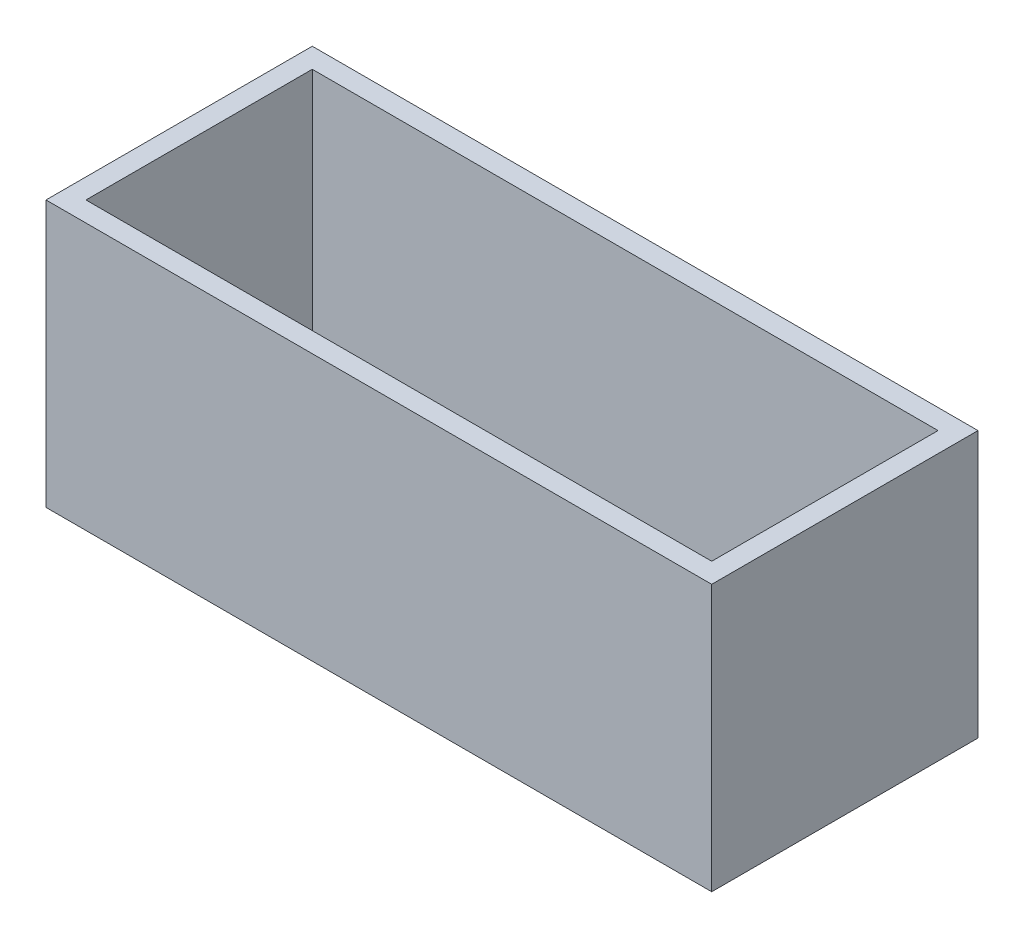
SolidWorks part; units mm, degrees
ref_plane "Front Plane" through (0, 0, 0) normal (0, 0, 1) x (1, 0, 0)
ref_plane "Top Plane" through (0, 0, 0) normal (0, 1, 0) x (1, 0, 0)
ref_plane "Right Plane" through (0, 0, 0) normal (1, 0, 0) x (0, 0, -1)
sketch "Sketch2" plane through (0, 0, 0) normal (0, 1, 0) x (1, 0, 0)
  line L1 (-50, -20) -> (50, -20)
  line L2 (-50, -20) -> (-50, 20)
  line L3 (-50, 20) -> (50, 20)
  line L4 (50, -20) -> (50, 20)
  line L5 (-50, -20) -> (50, 20) construction
  line L6 (-50, 20) -> (50, -20) construction
  point P0 (0, 0)
  dimension "D1" = 100
  dimension "D2" = 40
extrude "Boss-Extrude1" add sketch "Sketch2" along normal blind 40
ref_plane "Plane1" through (0, 40, 0) normal (0, 1, 0) x (1, 0, 0)
sketch "Sketch3" plane through (0, 40, 0) normal (0, 1, 0) x (1, 0, 0)
  line L0 (-50, 20) -> (-50, -20) construction
  line L1 (-47, -17) -> (47, -17)
  line L2 (-47, -17) -> (-47, 17)
  line L3 (-47, 17) -> (47, 17)
  line L4 (47, -17) -> (47, 17)
  line L5 (-47, -17) -> (47, 17) construction
  line L6 (-47, 17) -> (47, -17) construction
  line L7 (50, 20) -> (-50, 20) construction
  point P0 (0, 0)
  dimension "D1" = 3
  dimension "D2" = 3
extrude "Cut-Extrude1" cut sketch "Sketch3" against normal blind 37
